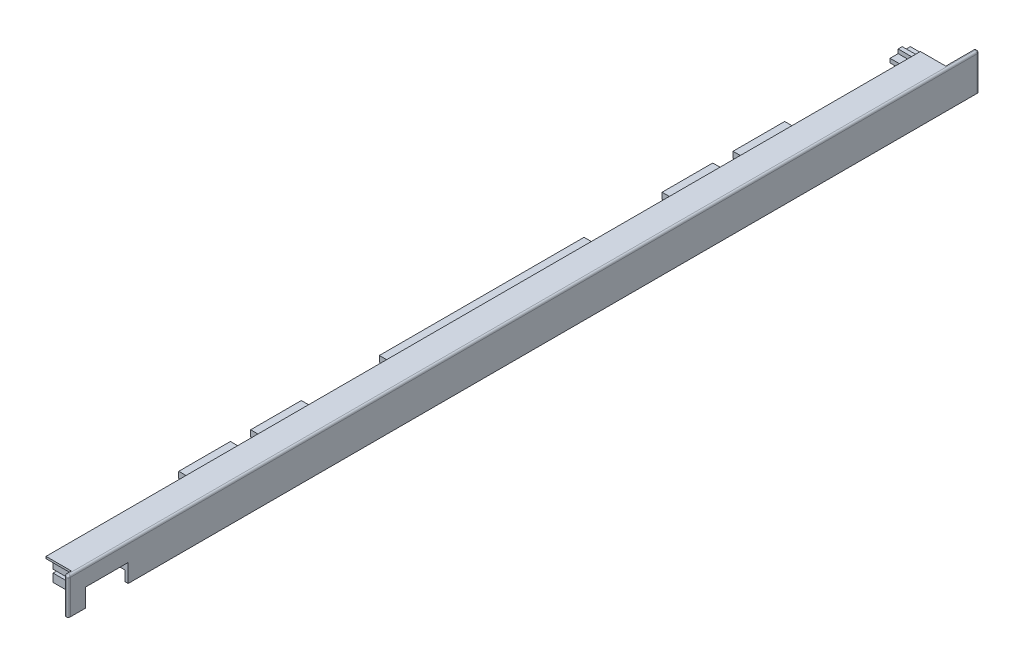
SolidWorks part; units mm, degrees
ref_plane "前视基准面" through (0, 0, 0) normal (0, 0, 1) x (1, 0, 0)
ref_plane "上视基准面" through (0, 0, 0) normal (0, 1, 0) x (1, 0, 0)
ref_plane "右视基准面" through (0, 0, 0) normal (1, 0, 0) x (0, 0, -1)
sketch "草图1" plane through (0, 0, 0) normal (0, 0, 1) x (1, 0, 0)
  line L0 (0, 0) -> (-14, 0)
  line L1 (-14, 0) -> (-14, -1)
  line L2 (-14, -1) -> (-1.5, -1)
  line L3 (-1.5, -1) -> (-1.5, -3.55)
  line L4 (-1.5, -3.55) -> (-14, -3.55)
  line L5 (-14, -3.55) -> (-14, -7.25)
  line L6 (-14, -7.25) -> (-1.5, -7.25)
  line L7 (-1.5, -7.25) -> (-1.5, -8.9)
  line L8 (-1.5, -8.9) -> (-14, -8.9)
  line L11 (0, -17.9) -> (0, 0)
  line L12 (-14, -8.9) -> (-14, -12.9)
  line L13 (-14, -12.9) -> (-1.5, -12.9)
  line L14 (-1.5, -12.9) -> (-1.5, -17.9)
  line L15 (-1.5, -17.9) -> (0, -17.9)
extrude "凸台-拉伸1" add sketch "草图1" along normal blind 449.532
sketch "草图7" plane through (-14, 0, 0) normal (-1, 0, 0) x (0, 0, 1)
  line L0 (0, 0) -> (15, 0)
  line L1 (449.532, 0) -> (0, 0) construction
  line L2 (15, 0) -> (15, -12.9)
  line L3 (449.532, -12.9) -> (0, -12.9) construction
  line L4 (15, -12.9) -> (0, -12.9)
  line L5 (0, -12.9) -> (0, 0)
extrude "切除-拉伸2" cut sketch "草图7" against normal blind 12.5
sketch "草图8" plane through (-14, 0, 0) normal (-1, 0, 0) x (0, 0, 1)
  line L0 (449.532, -12.9) -> (443.032, -12.9)
  line L1 (449.532, -12.9) -> (15, -12.9) construction
  line L3 (449.532, 0) -> (15, 0) construction
  line L6 (443.032, -1) -> (443.032, -12.9)
  line L9 (446.532, 0) -> (449.532, 0)
  line L10 (449.532, 0) -> (449.532, -12.9)
  line L11 (446.532, 0) -> (446.532, -1.0004)
  line L12 (446.532, -1.0004) -> (443.032, -1)
  line L13 (449.532, -1) -> (15, -1) construction
extrude "切除-拉伸3" cut sketch "草图8" against normal blind 12.5
sketch "草图10" plane through (-1.5, 0, 0) normal (-1, 0, 0) x (0, 0, 1)
  line L0 (6.5, -14.9) -> (6.5, -16.9)
  line L1 (12.5, -12.9) -> (12.5, -14.9)
  line L2 (8.5, -14.9) -> (8.5, -16.9)
  line L4 (12.5, -14.9) -> (8.5, -14.9)
  line L5 (2.5, -12.9) -> (2.5, -14.9)
  line L6 (2.5, -14.9) -> (6.5, -14.9)
  line L7 (8.5, -16.9) -> (6.5, -16.9)
  line L8 (12.5, -12.9) -> (8.5, -12.9)
  line L9 (8.5, -12.9) -> (8.5, -10.9)
  line L10 (8.5, -10.9) -> (6.5, -10.9)
  line L11 (6.5, -10.9) -> (6.5, -12.9)
  line L12 (6.5, -12.9) -> (2.5, -12.9)
  line L13 (64.5, -13.9) -> (90, -13.9)
  line L15 (64.5, -16.9) -> (90, -16.9)
  line L16 (90, -13.9) -> (90, -16.9)
  line L17 (264.517, -13.9) -> (264.517, -16.9)
  line L18 (100, -13.9) -> (100, -16.9)
  line L19 (100, -16.9) -> (125, -16.9)
  line L20 (100, -13.9) -> (125, -13.9)
  line L21 (125, -13.9) -> (125, -16.9)
  line L23 (163.517, -16.9) -> (264.517, -16.9)
  line L24 (163.517, -13.9) -> (264.517, -13.9)
  line L26 (303.032, -13.9) -> (303.032, -16.9)
  line L27 (303.032, -16.9) -> (328.032, -16.9)
  line L28 (303.032, -13.9) -> (328.032, -13.9)
  line L29 (328.032, -13.9) -> (328.032, -16.9)
  line L30 (338.032, -13.9) -> (338.032, -16.9)
  line L31 (338.032, -16.9) -> (363.532, -16.9)
  line L32 (338.032, -13.9) -> (363.532, -13.9)
  line L34 (163.517, -13.9) -> (163.517, -16.9)
  line L37 (64.5, -13.9) -> (64.5, -16.9)
  line L38 (363.532, -13.9) -> (363.532, -16.9)
extrude "凸台-拉伸6" add sketch "草图10" along normal blind 30
sketch "草图11" plane through (-1.5, 0, 0) normal (-1, 0, 0) x (0, 0, 1)
  line L2 (449.532, -17.9) -> (0, -17.9) construction
  line L4 (440.9789, -17.9) -> (419.9789, -17.9)
  line L6 (419.9789, -17.9) -> (419.9789, -8.9)
  line L7 (443.032, -8.9) -> (15, -8.9) construction
  line L8 (419.9789, -8.9) -> (440.9789, -8.9)
  line L9 (440.9789, -8.9) -> (440.9789, -17.9)
extrude "切除-拉伸4" cut sketch "草图11" against normal blind 30 and the other way blind 30
sketch "草图12" plane through (-14, 0, 0) normal (-1, 0, 0) x (0, 0, 1)
  line L0 (384.0289, -8.9) -> (384.0289, -12.9)
  line L1 (419.9789, -12.9) -> (15, -12.9) construction
  line L2 (414.0289, -12.9) -> (414.0289, -8.9)
  line L3 (419.9789, -8.9) -> (15, -8.9) construction
  line L4 (414.0289, -8.9) -> (384.0289, -8.9)
  line L5 (384.0289, -12.9) -> (414.0289, -12.9)
extrude "切除-拉伸5" cut sketch "草图12" against normal blind 12.5
sketch "草图15" plane through (-14, 0, 0) normal (-1, 0, 0) x (0, 0, 1)
  line L0 (31, -8.9) -> (38, -8.9)
  line L1 (384.0289, -8.9) -> (15, -8.9) construction
  line L2 (31, -8.9) -> (31, -10.9)
  line L3 (31, -10.9) -> (38, -10.9)
  line L4 (38, -8.9) -> (38, -10.9)
extrude "切除-拉伸8" cut sketch "草图15" against normal blind 12.5
sketch "草图17" plane through (-14, 0, 0) normal (-1, 0, 0) x (0, 0, 1)
  line L1 (384.0289, -8.9) -> (38, -8.9) construction
  line L2 (57, -8.9) -> (77, -8.9)
  line L3 (57, -8.9) -> (57, -11.4)
  line L4 (57, -11.4) -> (77, -11.4)
  line L5 (77, -11.4) -> (77, -8.9)
extrude "切除-拉伸9" cut sketch "草图17" against normal blind 12.5
fillet "圆角2" radius 1 1 edges at (0, 0, 224.766)
fillet "圆角3" radius 1 3 edges at (-1.25, 0, 0) (-0.2929, -0.2929, 0) (0, -9.45, 0)
fillet "圆角4" radius 1 3 edges at (-1.25, 0, 449.532) (-0.2929, -0.2929, 449.532) (0, -9.45, 449.532)
